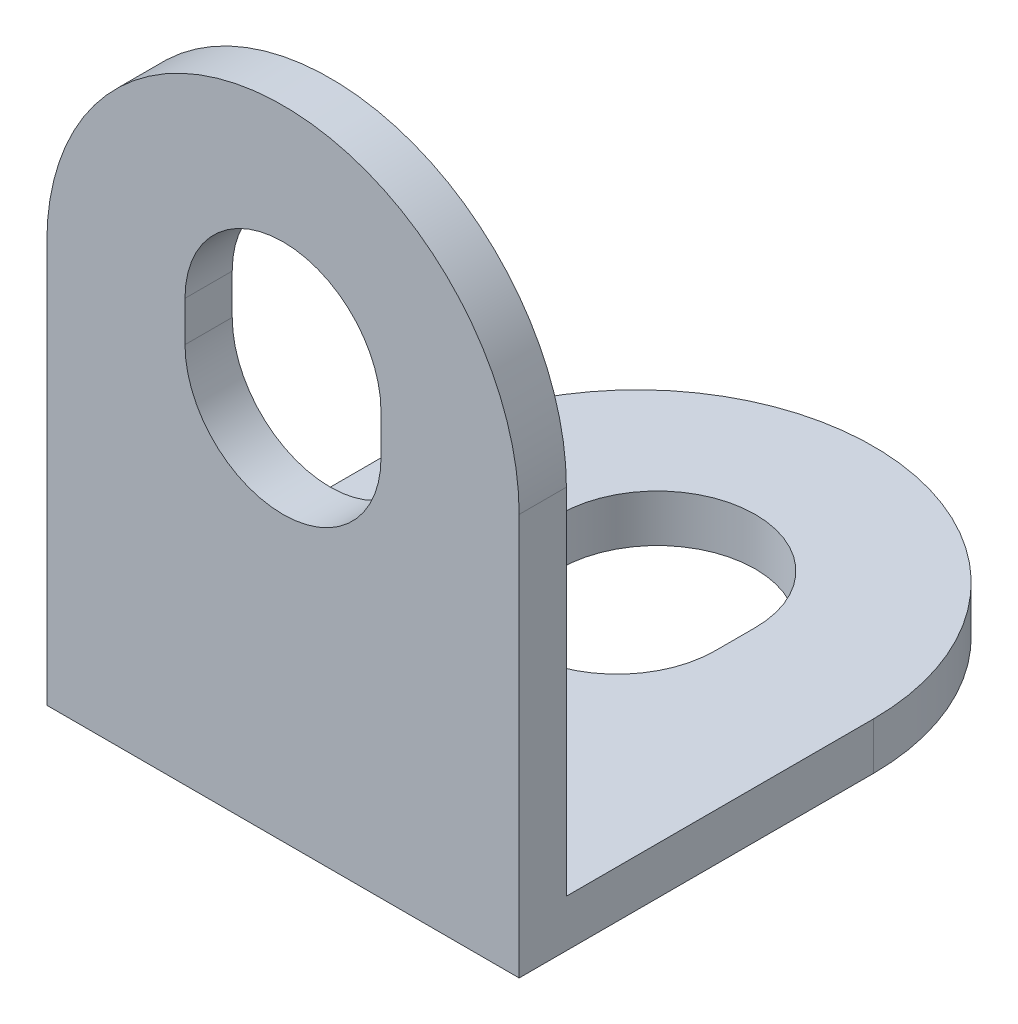
SolidWorks part; units mm, degrees
ref_plane "Front Plane" through (0, 0, 0) normal (0, 0, 1) x (1, 0, 0)
ref_plane "Top Plane" through (0, 0, 0) normal (0, 1, 0) x (1, 0, 0)
ref_plane "Right Plane" through (0, 0, 0) normal (1, 0, 0) x (0, 0, -1)
sketch "Sketch2" plane through (0, 0, 0) normal (0, 1, 0) x (1, 0, 0)
  line L0 (0, 0.425) -> (0, -0.425) construction
  line L2 (-5, 0) -> (-5, -7.5)
  line L3 (-5, -7.5) -> (5, -7.5)
  line L4 (5, 0) -> (5, -7.5)
  line L5 (2.075, 0.425) -> (2.075, -0.425)
  line L6 (-2.075, 0.425) -> (-2.075, -0.425)
  arc A0 (5, 0) -> (-5, 0) centre (0, 0) ccw
  arc A1 (2.075, 0.425) -> (-2.075, 0.425) centre (0, 0.425) ccw
  arc A2 (-2.075, -0.425) -> (2.075, -0.425) centre (0, -0.425) ccw
  point P8 (0, 0)
  point P13 (0, 0)
  point P16 (0, -2.5)
  dimension "D4" = 2.075
  dimension "D1" = 10
  dimension "D3" = 5
  dimension "D2" = 5
extrude "Boss-Extrude1" add sketch "Sketch2" along normal blind 1
pattern_circular "CirPattern1" count 2 every 90 about axis through (-5, 1, 7.5) along (1, 0, 0) of "Boss-Extrude1"
equation "\"Length\" = 1.5cm'Distance from corner to end"
equation "\"Width\"= 1cm'Width"
equation "\"ThicknessAll\" = 1mm'Thickness of the piece"
equation "\"D1@Boss-Extrude1\"=\"ThicknessAll\""
equation "\"D1@Sketch2\"=\"Width\""
equation "\"D3@Sketch2\"=\"EllipseLength\""
equation "\"SlotDiameter\"= 0.4cm + \"ErrorMargin\"'Width of hole"
equation "\"D4@Sketch2\"= \"SlotDiameter\" / 2"
equation "\"EllipseLength\"= 5mm"
equation "\"EllipseDist\"= 0.5cm'Distance of closest arc of ellipse from corner"
equation "\"D2@Sketch2\"=\"EllipseDist\""
equation "\"ErrorMargin\"= 0.15mm"
